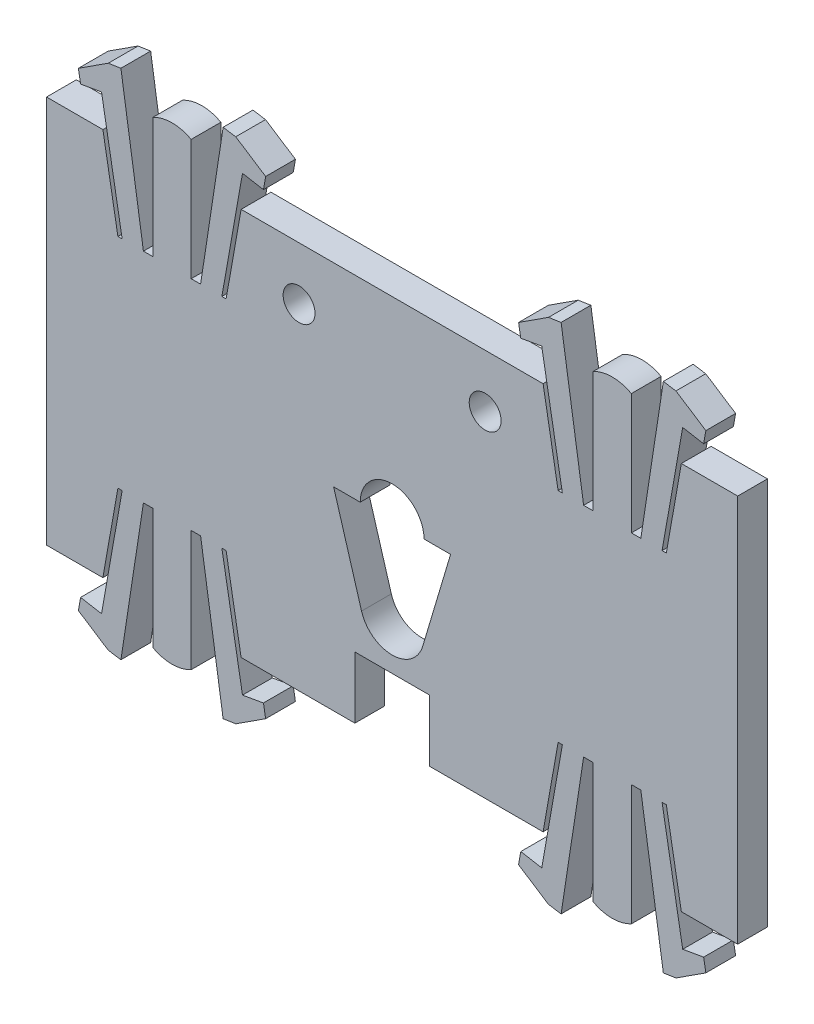
SolidWorks part; units mm, degrees
ref_plane "Přední rovina" through (0, 0, 0) normal (0, 0, 1) x (1, 0, 0)
ref_plane "Horní rovina" through (0, 0, 0) normal (0, 1, 0) x (1, 0, 0)
ref_plane "Pravá rovina" through (0, 0, 0) normal (1, 0, 0) x (0, 0, -1)
sketch "Model" plane through (0, 0, 0) normal (0, 0, 1) x (1, 0, 0)
  line L0 (-999.9987, 24.25) -> (49000.0013, 24.25) construction
  line L1 (-14.2, 18.25) -> (14.2, 18.25)
  line L2 (-27.2, -981.75) -> (-27.2, 49018.25) construction
  line L3 (-14.2, -981.75) -> (-14.2, 49018.25) construction
  line L4 (-20.7, -976.145) -> (-20.7, 49023.855) construction
  line L5 (32.5, 18.25) -> (27.2, 18.25)
  line L6 (25.7894, 10.25) -> (25.3894, 10.25)
  line L7 (25.7894, 10.25) -> (27.2, 18.25)
  line L8 (27.329, 21.25) -> (25.3894, 10.25)
  line L9 (29.2986, 20.9027) -> (27.329, 21.25)
  line L10 (29.2986, 20.9027) -> (29.507, 22.0845)
  line L11 (26.6932, 23.9074) -> (29.507, 22.0845)
  line L12 (25.507, 24.0889) -> (26.6932, 23.9074)
  line L13 (23.3894, 10.25) -> (25.507, 24.0889)
  line L19 (18.0106, 10.25) -> (15.893, 24.0889)
  line L20 (15.893, 24.0889) -> (14.7068, 23.9074)
  line L21 (14.7068, 23.9074) -> (11.893, 22.0845)
  line L25 (-1000, 10.25) -> (49000, 10.25) construction
  line L28 (-25.7894, 10.25) -> (-25.3894, 10.25)
  line L29 (-29.2986, 20.9027) -> (-29.507, 22.0845)
  line L30 (-25.507, 24.0889) -> (-26.6932, 23.9074)
  line L32 (-15.893, 24.0889) -> (-14.7068, 23.9074)
  line L33 (-14.7068, 23.9074) -> (-11.893, 22.0845)
  line L34 (-23.3894, 10.25) -> (-25.507, 24.0889)
  line L35 (-26.6932, 23.9074) -> (-29.507, 22.0845)
  line L36 (-29.2986, 20.9027) -> (-27.329, 21.25)
  line L37 (-27.329, 21.25) -> (-25.3894, 10.25)
  line L38 (-25.7894, 10.25) -> (-27.2, 18.25)
  line L39 (-27.2, 18.25) -> (-32.5, 18.25)
  line L40 (-12.1014, 20.9027) -> (-11.893, 22.0845)
  line L41 (-32.5, -18.25) -> (-32.5, 18.25)
  line L42 (32.5, -18.25) -> (32.5, 18.25)
  line L43 (-3.5, -12.45) -> (3.5, -12.45)
  line L44 (-27.2, -18.25) -> (-32.5, -18.25)
  line L45 (0, -7.95) -> (-2.875, -8.8069) construction
  line L46 (2.875, -8.8069) -> (5.5, 0)
  line L47 (5.5, 0) -> (3, 0)
  line L48 (-15.6106, -10.25) -> (-14.2, -18.25)
  line L49 (-15.6106, -10.25) -> (-16.0106, -10.25)
  line L50 (-14.071, -21.25) -> (-16.0106, -10.25)
  line L51 (-12.1014, -20.9027) -> (-14.071, -21.25)
  line L52 (-12.1014, -20.9027) -> (-11.893, -22.0845)
  line L53 (-14.7068, -23.9074) -> (-11.893, -22.0845)
  line L54 (-15.893, -24.0889) -> (-14.7068, -23.9074)
  line L56 (-18.0106, -10.25) -> (-15.893, -24.0889)
  line L58 (-14.2, -18.25) -> (-3.5, -18.25)
  line L59 (-3.5, -18.25) -> (-3.5, -12.45)
  line L63 (-23.3894, -10.25) -> (-25.507, -24.0889)
  line L64 (-25.507, -24.0889) -> (-26.6932, -23.9074)
  line L65 (-29.2986, -20.9027) -> (-29.507, -22.0845)
  line L66 (-26.6932, -23.9074) -> (-29.507, -22.0845)
  line L67 (-29.2986, -20.9027) -> (-27.329, -21.25)
  line L68 (-27.329, -21.25) -> (-25.3894, -10.25)
  line L69 (-25.7894, -10.25) -> (-27.2, -18.25)
  line L70 (-25.7894, -10.25) -> (-25.3894, -10.25)
  line L71 (27.2, -18.25) -> (32.5, -18.25)
  line L72 (25.7894, -10.25) -> (27.2, -18.25)
  line L73 (25.7894, -10.25) -> (25.3894, -10.25)
  line L74 (27.329, -21.25) -> (25.3894, -10.25)
  line L75 (29.2986, -20.9027) -> (27.329, -21.25)
  line L76 (29.2986, -20.9027) -> (29.507, -22.0845)
  line L77 (26.6932, -23.9074) -> (29.507, -22.0845)
  line L78 (25.507, -24.0889) -> (26.6932, -23.9074)
  line L79 (23.3894, -10.25) -> (25.507, -24.0889)
  line L81 (-2.875, -8.8069) -> (-5.5, 0)
  line L82 (-5.5, 0) -> (-3, 0)
  line L84 (0, -1000) -> (0, 49000) construction
  line L85 (-1000, 0) -> (49000, 0) construction
  line L86 (-12.1014, 20.9027) -> (-14.071, 21.25)
  line L87 (32.5, 18.25) -> (-32.5, 18.25) construction
  line L88 (32.5, 18.25) -> (32.5, -18.25) construction
  line L89 (32.5, -18.25) -> (-32.5, -18.25) construction
  line L90 (-32.5, 18.25) -> (-32.5, -18.25) construction
  line L91 (32.5, 18.25) -> (-32.5, -18.25) construction
  line L92 (32.5, -18.25) -> (-32.5, 18.25) construction
  line L95 (-18.0106, 10.25) -> (-15.893, 24.0889)
  line L96 (-14.071, 21.25) -> (-16.0106, 10.25)
  line L97 (-15.6106, 10.25) -> (-16.0106, 10.25)
  line L98 (-15.6106, 10.25) -> (-14.2, 18.25)
  line L99 (12.1014, 20.9027) -> (11.893, 22.0845)
  line L100 (12.1014, 20.9027) -> (14.071, 21.25)
  line L101 (14.071, 21.25) -> (16.0106, 10.25)
  line L102 (15.6106, 10.25) -> (16.0106, 10.25)
  line L103 (15.6106, 10.25) -> (14.2, 18.25)
  line L107 (18.0106, -10.25) -> (15.893, -24.0889)
  line L108 (15.893, -24.0889) -> (14.7068, -23.9074)
  line L109 (12.1014, -20.9027) -> (11.893, -22.0845)
  line L110 (14.7068, -23.9074) -> (11.893, -22.0845)
  line L111 (12.1014, -20.9027) -> (14.071, -21.25)
  line L112 (14.071, -21.25) -> (16.0106, -10.25)
  line L113 (15.6106, -10.25) -> (16.0106, -10.25)
  line L114 (15.6106, -10.25) -> (14.2, -18.25)
  line L115 (14.2, -18.25) -> (3.5, -18.25)
  line L116 (3.5, -18.25) -> (3.5, -12.45)
  line L121 (-22.5, 10.25) -> (-22.5, 21.5966)
  line L123 (-18.9, 10.25) -> (-18.9, 21.5966)
  line L128 (22.5, 10.25) -> (22.5, 21.5966)
  line L129 (18.9, 10.25) -> (18.9, 21.5966)
  line L132 (22.5, -10.25) -> (22.5, -21.5966)
  line L135 (18.9, -10.25) -> (18.9, -21.5966)
  line L138 (-18.9, -10.25) -> (-18.9, -21.5966)
  line L141 (-22.5, -10.25) -> (-22.5, -21.5966)
  line L142 (-22.5, 10.25) -> (-23.3894, 10.25)
  line L143 (-18.9, 10.25) -> (-18.0106, 10.25)
  line L144 (18.9, 10.25) -> (18.0106, 10.25)
  line L145 (22.5, 10.25) -> (23.3894, 10.25)
  line L146 (22.5, -10.25) -> (23.3894, -10.25)
  line L147 (18.9, -10.25) -> (18.0106, -10.25)
  line L148 (-18.9, -10.25) -> (-18.0106, -10.25)
  line L149 (-22.5, -10.25) -> (-23.3894, -10.25)
  line L150 (-10.6253, 11.75) -> (-7.157, 11.75) construction
  circle A0 centre (-8.75, 13.25) radius 1.5
  circle A1 centre (8.75, 13.25) radius 1.5
  circle A2 centre (0, -7.95) radius 3 construction
  circle A4 centre (0, 0) radius 3 construction
  arc A5 (-3, 0) -> (3, 0) centre (0, 0) cw
  arc A6 (-2.875, -8.8069) -> (2.875, -8.8069) centre (0, -7.95) ccw
  arc A7 (-24.5, 18.25) -> (-16.9, 18.25) centre (-20.7, 18.25) cw construction
  arc A12 (22.5, 21.5966) -> (18.9, 21.5966) centre (20.7, 18.25) ccw
  arc A15 (22.5, -21.5966) -> (18.9, -21.5966) centre (20.7, -18.25) cw
  arc A18 (-22.5, -21.5966) -> (-18.9, -21.5966) centre (-20.7, -18.25) ccw
  arc A19 (-22.5, 21.5966) -> (-18.9, 21.5966) centre (-20.7, 18.25) cw
  point P1 (0, 18.25)
  point P14 (0, 0)
  point P27 (-10.6253, 11.75)
  point P104 (0, -12.45)
  point P268 (0, 0)
  dimension "D17" = 30
  dimension "D19" = 3
  dimension "D22" = 4.5
  dimension "D23" = 6
  dimension "D24" = 6
  dimension "D26" = 1.8
  dimension "D14" = 3.8
  dimension "D27" = 5.5
  dimension "D1" = 65
  dimension "D2" = 36.5
  dimension "D3" = 6
  dimension "D4" = 13
  dimension "D5" = 14.2
  dimension "D6" = 0.4
  dimension "D7" = 8
  dimension "D8" = 2
  dimension "D9" = 80
  dimension "D10" = 2
  dimension "D11" = 3
  dimension "D12" = 2.6527
  dimension "D13" = 1.2
  dimension "D15" = 1.2
  dimension "D16" = 14
  dimension "D18" = 8.75
  dimension "D20" = 3.5
  dimension "D21" = 5.8
  dimension "D29" = 81.3
extrude "Přidat vysunutím1" add sketch "Model" along normal blind 2.8
